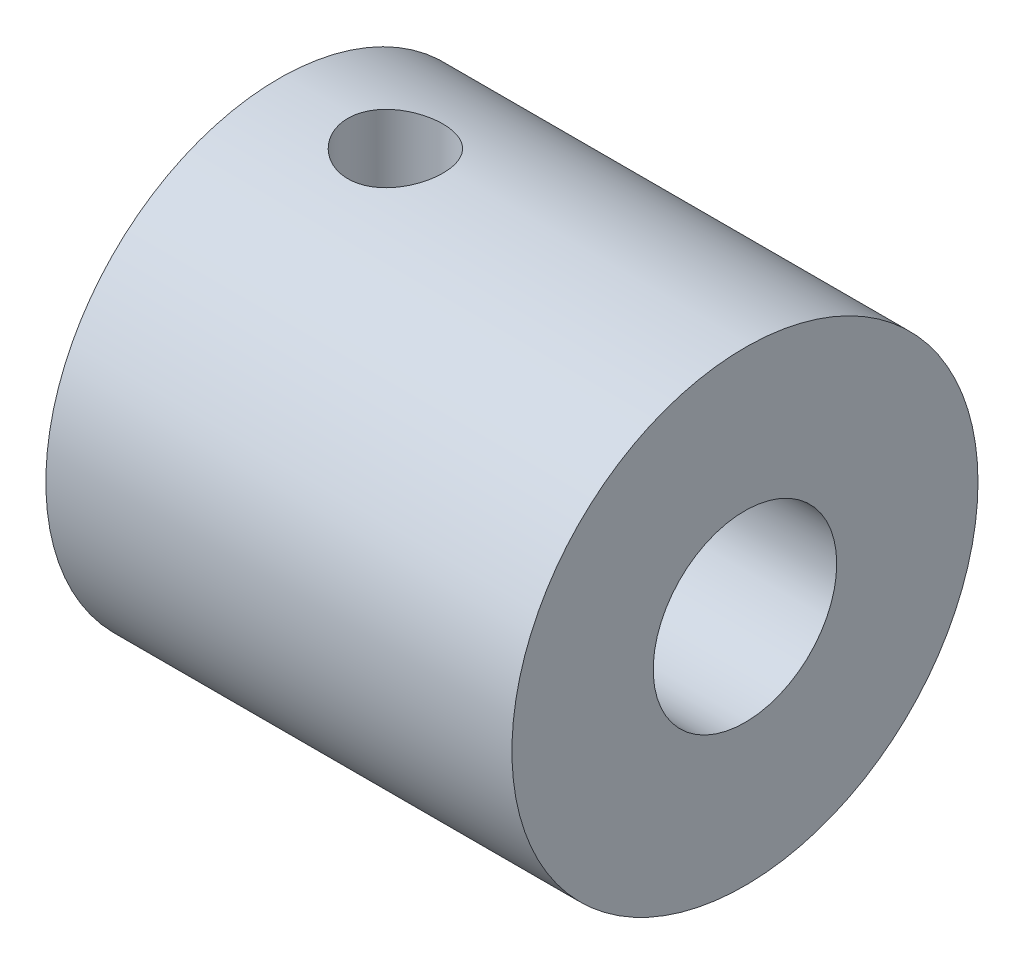
SolidWorks part; units mm, degrees
material "201 Annealed Stainless Steel (SS)"
ref_plane "Front Plane" through (0, 0, 0) normal (0, 0, 1) x (1, 0, 0)
ref_plane "Top Plane" through (0, 0, 0) normal (0, 1, 0) x (1, 0, 0)
ref_plane "Right Plane" through (0, 0, 0) normal (1, 0, 0) x (0, 0, -1)
sketch "Sketch1" plane through (0, 0, 0) normal (1, 0, 0) x (0, 0, -1)
  circle A0 centre (0, 0) radius 12.7
  dimension "D1" = 25.4
extrude "Boss-Extrude1" add sketch "Sketch1" along normal blind 25.4
sketch "Sketch2" plane through (0, 0, 0) normal (-1, 0, 0) x (0, 0, 1)
  circle A0 centre (0, 0) radius 3
  dimension "D1" = 6
extrude "Cut-Extrude1" cut sketch "Sketch2" against normal blind 9.525
sketch "Sketch3" plane through (25.4, 0, 0) normal (1, 0, 0) x (0, 0, -1)
  circle A0 centre (0, 0) radius 5
  point P0 (0, 0)
  dimension "D1" = 10
sketch "Sketch6" plane through (0, 0, 0) normal (0, 1, 0) x (1, 0, 0)
  point P0 (6.35, 0)
  dimension "D1" = 6.35
hole_wizard "#6 (0.204) Diameter Hole1" positions "Sketch8" profile "Sketch7" hole size "#6" standard "ANSI Inch"
sketch "Sketch8" plane through (0, 0, 0) normal (0, 1, 0) x (1, 0, 0)
  point P0 (6.35, 0)
sketch "Sketch7" plane through (6.35, 0, 0) normal (1, 0, 0) x (0, 0, -1)
  line L0 (0, 0) -> (0, 16.2887)
  line L1 (0, 16.2887) -> (2.5908, 14.732)
  line L2 (2.5908, 14.732) -> (2.5908, 0)
  line L5 (2.5908, 0) -> (0, 0)
  line L10 (0, 16.2887) -> (-2.5908, 14.732) construction
  line L11 (0, -6.35) -> (0, 107.95) construction
  dimension "Hole Dia." = 5.1816
  dimension "Hole Depth" = 14.732
  dimension "Drill Angle" = 118
extrude "Cut-Extrude2" cut sketch "Sketch3" against normal blind 9.525
